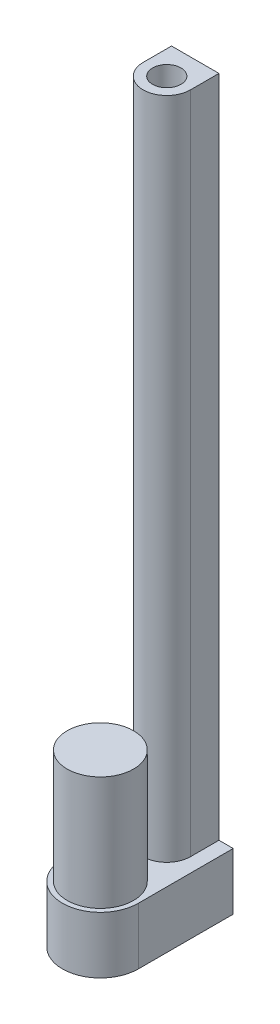
SolidWorks part; units mm, degrees
ref_plane "Frontal Plane" through (0, 0, 0) normal (0, 0, 1) x (1, 0, 0)
ref_plane "Horizontal Plane" through (0, 0, 0) normal (0, 1, 0) x (1, 0, 0)
ref_plane "Profile Plane" through (0, 0, 0) normal (1, 0, 0) x (0, 0, -1)
sketch "Sketch1" plane through (0, 0, 0) normal (0, 1, 0) x (1, 0, 0)
  line L0 (-20, -50) -> (-20, 0)
  line L1 (20, 0) -> (20, -50)
  line L2 (-20, 0) -> (20, 0)
  arc A1 (20, -50) -> (-20, -50) centre (0, -50) cw
  point P3 (0, 0)
  dimension "D2" = 40
  dimension "D1" = 50
extrude "Boss-Extrude1" add sketch "Sketch1" along normal blind 30
ref_plane "Plane1" through (0, 30, 0) normal (0, 1, 0) x (1, 0, 0)
sketch "Sketch2" plane through (0, 30, 0) normal (0, 1, 0) x (1, 0, 0)
  circle A0 centre (0, -50) radius 17.5
  dimension "D1" = 35
extrude "Boss-Extrude2" add sketch "Sketch2" along normal blind 60
sketch "Sketch3" plane through (0, 30, 0) normal (0, 1, 0) x (1, 0, 0)
  line L0 (-12.5, 0) -> (-12.5, -15)
  line L1 (12.5, -15) -> (12.5, 0)
  line L2 (-12.5, 0) -> (12.5, 0)
  arc A1 (-12.5, -15) -> (12.5, -15) centre (0, -15) ccw
  point P0 (0, 0)
  dimension "D1" = 25
  dimension "D2" = 15
extrude "Boss-Extrude3" add sketch "Sketch3" along normal blind 350
ref_plane "Plane2" through (0, 380, 0) normal (0, 1, 0) x (1, 0, 0)
sketch "Sketch4" plane through (0, 380, 0) normal (0, 1, 0) x (1, 0, 0)
  circle A0 centre (0, -15) radius 7.5
  dimension "D1" = 15
extrude "Cut-Extrude1" cut sketch "Sketch4" against normal blind 350 and the other way through all
ref_plane "Plane3" through (0, 0, 0) normal (0, -1, 0) x (-1, 0, 0)
sketch "Sketch5" plane through (0, 0, 0) normal (0, -1, 0) x (-1, 0, 0)
  line L0 (-20, 0) -> (20, 0) construction
  line L1 (-5, -5) -> (5, -5)
  line L2 (-5, -5) -> (-5, -15)
  line L3 (-5, -15) -> (5, -15)
  line L4 (5, -5) -> (5, -15)
  line L5 (-5, -5) -> (5, -15) construction
  line L6 (-5, -15) -> (5, -5) construction
  point P0 (0, -10)
  dimension "D1" = 10
  dimension "D2" = 10
  dimension "D3" = 5
extrude "Boss-Extrude4" add sketch "Sketch5" along normal blind 15
ref_plane "Plane4" through (5, 0, 0) normal (1, 0, 0) x (0, 0, -1)
sketch "Sketch6" plane through (5, 0, 0) normal (1, 0, 0) x (0, 0, -1)
  line L0 (-5, -15) -> (-15, -15) construction
  circle A0 centre (-10, -10) radius 3
  point P6 (-10, -15)
  dimension "D1" = 6
  dimension "D2" = 5
extrude "Cut-Extrude2" cut sketch "Sketch6" against normal through all
equation "\"PinDiameter\"= 1cm"
equation "\"WallThickness\"= 0.5cm"
equation "\"ActuatorL\"= 35cm"
equation "\"Box-X\"= 40cm"
equation "\"Box-Z\"= 20cm"
equation "\"Box-Y\"= 30cm"
equation "\"BottomPlateX\"= 100cm"
equation "\"ArmPlateX\"= 40cm"
equation "\"Arm1X\"= 5cm"
equation "\"Arm1L\"= 60cm"
equation "\"Arm2GAP\"= 5cm"
equation "\"Arm2L\"= 60cm"
equation "\"Arm2H\"= 5cm"
equation "\"Arm2Extension\"= 5cm"
equation "\"Arm3GAP\"= 5cm"
equation "\"Arm3L\"= 60cm"
equation "\"Arm3H\"= 5cm"
equation "\"Pin1-2L\"= \"Arm2GAP\" + (2 * \"WallThickness\")"
equation "\"Pin2-3L\"= \"Arm3GAP\" + (4 * \"WallThickness\")"
equation "\"D1@Boss-Extrude3\"=\"ActuatorL\""
equation "\"D1@Cut-Extrude1\"=\"ActuatorL\""
equation "\"RotaryUnionThickness\"= 1cm"
equation "\"ArmPlateThickness\"= 1cm"
equation "\"DCMotor1D\"= 65mm"
equation "\"DCMotor1L\"= 20cm"
equation "\"DCMotor1ShaftL\"= \"ArmPlateThickness\" + 1.7cm"
equation "\"DCMotor2X\"= 57mm"
equation "\"DCMotor2D\"= 57mm"
equation "\"DCMotor2L\"= 153mm"
equation "\"DCMotor2ShaftL\"= 34mm"
equation "\"BenchDepth\"= 5cm"
equation "\"BenchH\"= 10cm"
equation "\"BenchL\"= 15cm"
equation "\"ActuatorPinD\"= 6mm"
equation "\"D1@Sketch6\"=\"ActuatorPinD\""
